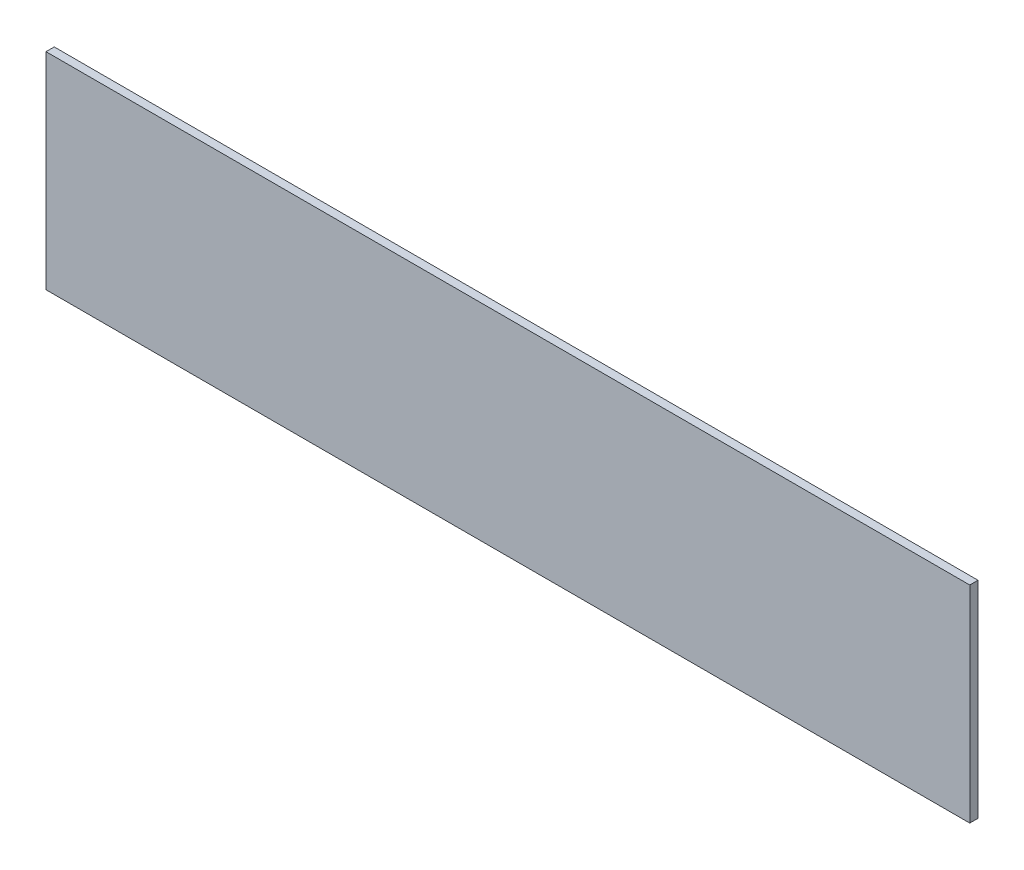
SolidWorks part; units mm, degrees
ref_plane "Front Plane" through (0, 0, 0) normal (0, 0, 1) x (1, 0, 0)
ref_plane "Top Plane" through (0, 0, 0) normal (0, 1, 0) x (1, 0, 0)
ref_plane "Right Plane" through (0, 0, 0) normal (1, 0, 0) x (0, 0, -1)
sketch "Sketch1" plane through (0, 0, 0) normal (0, 0, 1) x (1, 0, 0)
  line L1 (-112, 25) -> (112, 25)
  line L2 (-112, 25) -> (-112, -25)
  line L3 (-112, -25) -> (112, -25)
  line L4 (112, 25) -> (112, -25)
  line L5 (-112, 25) -> (112, -25) construction
  line L6 (-112, -25) -> (112, 25) construction
  point P0 (0, 0)
  dimension "D1" = 50
  dimension "D2" = 224
extrude "Boss-Extrude1" add sketch "Sketch1" along normal mid plane 2
